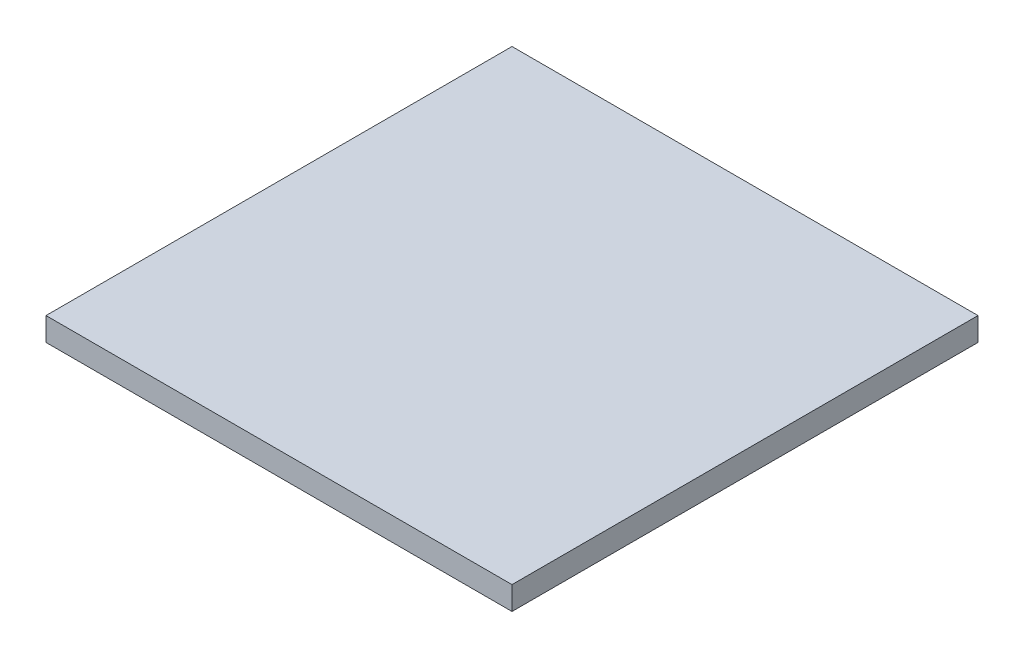
SolidWorks part; units mm, degrees
material "Concreto"
ref_plane "Alzado" through (0, 0, 0) normal (0, 0, 1) x (1, 0, 0)
ref_plane "Planta" through (0, 0, 0) normal (0, 1, 0) x (1, 0, 0)
ref_plane "Vista lateral" through (0, 0, 0) normal (1, 0, 0) x (0, 0, -1)
sketch "Croquis1" plane through (0, 0, 0) normal (0, 1, 0) x (1, 0, 0)
  line L1 (0, 0) -> (6000, 0)
  line L2 (0, 0) -> (0, 6000)
  line L3 (0, 6000) -> (6000, 6000)
  line L4 (6000, 0) -> (6000, 6000)
  dimension "D1" = 6000
  dimension "D2" = 6000
extrude "Saliente-Extruir1" add sketch "Croquis1" along normal blind 300
